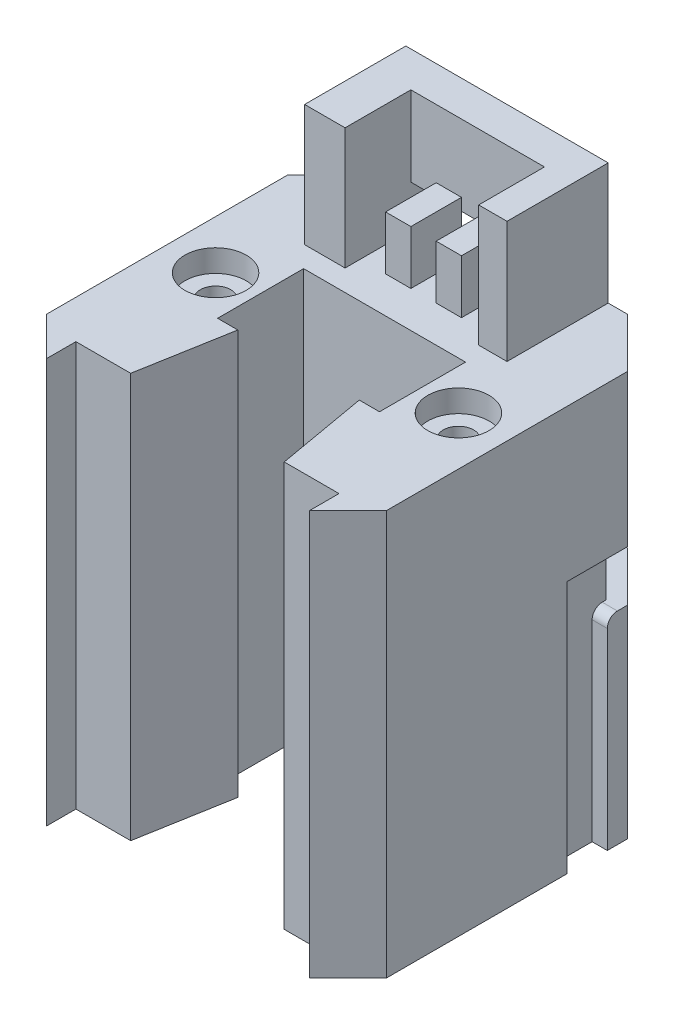
SolidWorks part; units mm, degrees
ref_plane "前视基准面" through (0, 0, 0) normal (0, 0, 1) x (1, 0, 0)
ref_plane "上视基准面" through (0, 0, 0) normal (0, 1, 0) x (1, 0, 0)
ref_plane "右视基准面" through (0, 0, 0) normal (1, 0, 0) x (0, 0, -1)
sketch "草图1" plane through (0, 0, 0) normal (0, 1, 0) x (1, 0, 0)
  line L0 (0, 0) -> (31, 0) construction
  line L1 (0, 0) -> (24.3952, -24.3952) construction
  line L2 (-31, 12) -> (-31, -12) construction
  line L3 (-32.8805, 15.9099) -> (-15.9099, 32.8805) construction
  line L4 (-24.3952, 24.3952) -> (0, 0) construction
  line L5 (-31, 0) -> (0, 0) construction
  line L6 (-43, 22.7609) -> (-43, -22.7609) construction
  line L7 (-43, 22.7609) -> (-22.7609, 43) construction
  line L8 (-24.3952, 24.3952) -> (-32.8805, 32.8805) construction
  line L9 (-31, 0) -> (-43, 0) construction
  line L10 (22.7609, 43) -> (43, 22.7609) construction
  line L11 (22.7609, 43) -> (-22.7609, 43) construction
  line L12 (43, -22.7609) -> (22.7609, -43) construction
  line L13 (43, -22.7609) -> (43, 22.7609) construction
  line L14 (-22.7609, -43) -> (-43, -22.7609) construction
  line L15 (-22.7609, -43) -> (22.7609, -43) construction
  line L16 (24.0036, 46) -> (-24.0036, 46) construction
  line L17 (-46, 24.0036) -> (-24.0036, 46) construction
  line L18 (-46, 24.0036) -> (-46, -24.0036) construction
  line L19 (-24.0036, -46) -> (-46, -24.0036) construction
  line L20 (-24.0036, -46) -> (24.0036, -46) construction
  line L21 (46, -24.0036) -> (24.0036, -46) construction
  line L22 (46, -24.0036) -> (46, 24.0036) construction
  line L23 (24.0036, 46) -> (46, 24.0036) construction
  line L24 (11.9085, 16.8) -> (-11.9085, 16.8)
  line L25 (-16.8, 11.9085) -> (-11.9085, 16.8)
  line L26 (-16.8, 11.9085) -> (-16.8, -11.9085)
  line L27 (-11.9085, -16.8) -> (-16.8, -11.9085)
  line L28 (-11.9085, -16.8) -> (11.9085, -16.8)
  line L29 (16.8, -11.9085) -> (11.9085, -16.8)
  line L30 (16.8, -11.9085) -> (16.8, 11.9085)
  line L31 (11.9085, 16.8) -> (16.8, 11.9085)
  circle A0 centre (0, 0) radius 15 construction
  circle A1 centre (31, 0) radius 12 construction
  circle A2 centre (24.3952, -24.3952) radius 12 construction
  circle A3 centre (0, -31) radius 12 construction
  circle A4 centre (-24.3952, -24.3952) radius 12 construction
  circle A5 centre (-31, 0) radius 12 construction
  circle A6 centre (-24.3952, 24.3952) radius 12 construction
  circle A7 centre (0, 31) radius 12 construction
  circle A8 centre (24.3952, 24.3952) radius 12 construction
  point P22 (0, 0)
  point P41 (0, 0)
  dimension "D1" = 30
  dimension "D2" = 24
  dimension "D3" = 31
  dimension "D4" = 34.5
  dimension "D5" = 45
  dimension "D8" = 3
  dimension "D9" = 26.2
  dimension "D6" = 4
  dimension "D7" = 4
extrude "凸台-拉伸1" add sketch "草图1" along normal blind 40
sketch "草图2" plane through (0, 40, 0) normal (0, 1, 0) x (1, 0, 0)
  line L0 (0, 0) -> (12, 0) construction
  line L1 (0, 0) -> (0, 18.2008) construction
  circle A0 centre (12, 0) radius 1.5
  circle A1 centre (-12, 0) radius 1.5
  dimension "D1" = 3
  dimension "D2" = 24
extrude "切除-拉伸1" cut sketch "草图2" against normal through all
sketch "草图3" plane through (0, 40, 0) normal (0, 1, 0) x (1, 0, 0)
  line L0 (0, 0) -> (0, -22.2905) construction
  line L1 (-6, -3.8) -> (6, -3.8)
  line L2 (6, -3.8) -> (7.5869, -12.8)
  line L3 (7.5869, -12.8) -> (13, -12.8)
  line L4 (13, -12.8) -> (13, -16.8)
  line L5 (-11.9085, -16.8) -> (11.9085, -16.8) construction
  line L6 (13, -16.8) -> (-13, -16.8)
  line L7 (-13, -12.8) -> (-13, -16.8)
  line L8 (-7.5869, -12.8) -> (-13, -12.8)
  line L9 (-6, -3.8) -> (-7.5869, -12.8)
  point P3 (11.3119, -16.8)
  point P12 (0, -16.8)
  point P15 (0, -3.8)
  point P16 (6, 3.6108)
  point P17 (6, 3.2457)
  point P18 (6, -4.8919)
  dimension "D1" = 13
  dimension "D2" = 12
  dimension "D3" = 4
  dimension "D4" = 26
  dimension "D5" = 100
extrude "切除-拉伸2" cut sketch "草图3" against normal through all
sketch "草图4" plane through (0, 40, 0) normal (0, 1, 0) x (1, 0, 0)
  line L0 (0, 0) -> (0, 19.1016) construction
  line L1 (11.9085, 16.8) -> (-11.9085, 16.8) construction
  line L2 (-10, 6.8) -> (10, 6.8)
  line L3 (-10, 6.8) -> (-10, 16.8)
  line L4 (-10, 16.8) -> (10, 16.8)
  line L5 (10, 6.8) -> (10, 16.8)
  line L6 (-10, 6.8) -> (10, 16.8) construction
  line L7 (-10, 16.8) -> (10, 6.8) construction
  line L9 (-6, 6.8) -> (7.2, 6.8)
  line L10 (-6, 6.8) -> (-6, 13.3)
  line L11 (-6, 13.3) -> (7.2, 13.3)
  line L12 (7.2, 6.8) -> (7.2, 13.3)
  point P3 (0, 11.8)
  line M13 (11.9085, 16.8) -> (-11.9085, 16.8)
  dimension "D1" = 20
  dimension "D2" = 10
  dimension "D3" = 3.5
  dimension "D4" = 13.2
  dimension "D5" = 4
extrude "凸台-拉伸2" add sketch "草图4" along normal blind 12 contours L12 L2 L5 L3 L10 L11 M13
sketch "草图5" plane through (0, 40, 0) normal (0, 1, 0) x (1, 0, 0)
  line L0 (0, 0) -> (0, 7.6634) construction
  line L1 (6, -3.8) -> (-6, -3.8) construction
  line L2 (-6, 4.7) -> (6, 4.7)
  line L3 (-6, 4.7) -> (-6, -3.8)
  line L4 (-6, -3.8) -> (6, -3.8)
  line L5 (6, 4.7) -> (6, -3.8)
  line L6 (-6, 4.7) -> (6, -3.8) construction
  line L7 (-6, -3.8) -> (6, 4.7) construction
  point P3 (0, 0.45)
  dimension "D1" = 12
  dimension "D2" = 8.5
extrude "切除-拉伸3" cut sketch "草图5" against normal through all
sketch "草图6" plane through (0, 0, 0) normal (0, -1, 0) x (1, 0, 0)
  line L0 (-6, -13.3) -> (7.2, -13.3) construction
  line L1 (-6, -13.3) -> (7.2, -13.3) construction
  line L2 (-6, -6.8) -> (-6, -13.3) construction
  line L3 (-6, -6.8) -> (-6, -13.3)
  line L4 (7.2, -6.8) -> (7.2, -13.3) construction
  line L5 (7.2, -6.8) -> (7.2, -13.3)
  line L6 (-6, -6.8) -> (-6, -4.7) construction
  line L7 (-6, -4.7) -> (6, -4.7) construction
  line L8 (6, -4.7) -> (7.2, -6.8) construction
  line L9 (-6, -6.8) -> (7.2, -6.8)
  line L10 (-6, -13.3) -> (-6, -16.8)
  line L11 (11.9085, -16.8) -> (-11.9085, -16.8) construction
  line L12 (-6, -16.8) -> (7.2, -16.8)
  line L13 (7.2, -16.8) -> (7.2, -13.3)
extrude "切除-拉伸4" cut sketch "草图6" against normal blind 12
sketch "草图7" plane through (0, 40, 0) normal (0, 1, 0) x (1, 0, 0)
  line L0 (-6, 13.3) -> (7.2, 13.3) construction
  line L1 (4, 13.3) -> (1.5, 13.3)
  line L2 (4, 13.3) -> (4, 8.3)
  line L3 (4, 8.3) -> (1.5, 8.3)
  line L4 (1.5, 13.3) -> (1.5, 8.3)
  line L6 (-1, 13.3) -> (-3.5, 13.3)
  line L7 (-1, 13.3) -> (-1, 8.3)
  line L8 (-1, 8.3) -> (-3.5, 8.3)
  line L9 (-3.5, 13.3) -> (-3.5, 8.3)
  line L10 (-6, 6.8) -> (-6, 13.3) construction
  dimension "D1" = 2.5
  dimension "D2" = 2.5
  dimension "D3" = 2.5
  dimension "D4" = 5
extrude "凸台-拉伸3" add sketch "草图7" along normal blind 5.3
sketch "草图8" plane through (0, 12, 0) normal (0, -1, 0) x (1, 0, 0)
  line L1 (-3.5, -11.8) -> (-1, -11.8)
  line L2 (-3.5, -11.8) -> (-3.5, -6.8)
  line L3 (-3.5, -6.8) -> (-1, -6.8)
  line L4 (-1, -11.8) -> (-1, -6.8)
  line L5 (-6, -6.8) -> (-6, -16.8) construction
  line L6 (1.5, -11.8) -> (4, -11.8)
  line L7 (1.5, -11.8) -> (1.5, -6.8)
  line L8 (1.5, -6.8) -> (4, -6.8)
  line L9 (4, -11.8) -> (4, -6.8)
  line L10 (7.2, -6.8) -> (-6, -6.8) construction
  point P4 (-3.5, -6.8)
  point P12 (0, 0)
  point P13 (0, 0)
  point P15 (1.5, -6.8)
  dimension "D1" = 2.5
  dimension "D2" = 2.5
  dimension "D3" = 2.5
  dimension "D4" = 5
extrude "凸台-拉伸4" add sketch "草图8" along normal blind 5.2
sketch "草图10" plane through (0, 40, 0) normal (0, 1, 0) x (1, 0, 0)
  line L0 (6, 0.45) -> (-6, 0.45) construction
  line L1 (6, -3.8) -> (6, 4.7) construction
  line L2 (-6, 4.7) -> (-6, -3.8) construction
  line L3 (6, 4.7) -> (-6, 4.7) construction
  line L4 (-8, -3.8) -> (8, -3.8)
  line L5 (-8, -3.8) -> (-8, 4.7)
  line L6 (-8, 4.7) -> (8, 4.7)
  line L7 (8, -3.8) -> (8, 4.7)
  line L8 (-8, -3.8) -> (8, 4.7) construction
  line L9 (-8, 4.7) -> (8, -3.8) construction
  point P6 (0, 0.45)
  point P11 (0, 0)
  dimension "D1" = 16
extrude "切除-拉伸5" cut sketch "草图10" against normal through all
sketch "草图11" plane through (0, 0, -13.3) normal (0, 0, 1) x (1, 0, 0)
  line L1 (-6, 52) -> (-6, 40) construction
  line L2 (1.5, 45.3) -> (-6, 45.3)
  line L3 (1.5, 45.3) -> (1.5, 40)
  line L4 (1.5, 40) -> (-6, 40)
  line L5 (-6, 45.3) -> (-6, 40)
  line L6 (-6, 44.1) -> (1.5, 44.1)
  dimension "D1" = 1.2
extrude "切除-拉伸6" cut sketch "草图11" against normal blind 11
sketch "草图15" plane through (0, 0, -16.8) normal (0, 0, -1) x (-1, 0, 0)
  line L0 (-1.5, 6.8) -> (-1.5, 12) construction
  line L1 (-1.5, 6.8) -> (-1.5, 12) construction
  line L2 (6, 12) -> (6, 0) construction
  line L3 (6, 12) -> (6, 0) construction
  line L5 (-1.5, 12) -> (6, 12)
  line L6 (-1.5, 12) -> (-1.5, 17)
  line L7 (-1.5, 17) -> (6, 17)
  line L8 (6, 12) -> (6, 17)
  point P7 (6.2201, 12)
  dimension "D1" = 5
extrude "切除-拉伸10" cut sketch "草图15" against normal up to surface (10 mm away) up to face at (0.3667, 8.2667, -6.8)
sketch "草图12" plane through (0, 40, 0) normal (0, 1, 0) x (1, 0, 0)
  line L0 (-6, 6.8) -> (-6, 16.8) construction
  line L1 (1.5, 16.8) -> (-6, 16.8)
  line L2 (1.5, 16.8) -> (1.5, 15.3)
  line L3 (1.5, 15.3) -> (-6, 15.3)
  line L4 (-6, 16.8) -> (-6, 15.3)
  dimension "D1" = 1.5
extrude "切除-拉伸7" cut sketch "草图12" against normal up to surface (28 mm away) up to face at (4.2333, 12, -11.8)
sketch "草图13" plane through (0, 0, 0) normal (0, -1, 0) x (1, 0, 0)
  line L0 (11.9085, -16.8) -> (1.5, -16.8)
  line L1 (1.5, -16.8) -> (7.2, -16.8) construction
  line L18 (1.5, -16.8) -> (7.2, -16.8) construction
  line L19 (11.9085, -16.8) -> (16.8, -11.9085)
  line L20 (16.8, -11.9085) -> (16.8, -5.9085)
  line L21 (16.8, 11.9085) -> (16.8, -11.9085) construction
  line L22 (15.3, -11.2872) -> (15.3, -5.9085)
  line L23 (11.2872, -15.3) -> (15.3, -11.2872)
  line L24 (11.2872, -15.3) -> (1.5, -15.3)
  line L25 (16.8, -5.9085) -> (15.3, -5.9085)
  line L26 (1.5, -16.8) -> (1.5, -15.3)
  dimension "D1" = 6
  dimension "D2" = 1.5
extrude "切除-拉伸8" cut sketch "草图13" against normal blind 5 from offset 20 offset against normal yes
fillet "圆角2" radius 2 1 edges at (-2.25, 17, -15.3)
sketch "草图16" plane through (0, 40, 0) normal (0, 1, 0) x (1, 0, 0)
  circle A0 centre (12, 0) radius 3.025
  circle A1 centre (-12, 0) radius 3.025
  dimension "D1" = 6.05
extrude "切除-拉伸11" cut sketch "草图16" against normal blind 2.2
ref_plane "基准面1" through (0, 20, 0) normal (0, 1, 0) x (1, 0, 0)
mirror "镜向1" about plane through (0, 20, 0) normal (0, 1, 0) of "切除-拉伸11"
sketch "草图17" plane through (0, 20, 0) normal (0, 1, 0) x (1, 0, 0)
  line L5 (15.3, 5.9085) -> (15.3, 11.2872) construction
  line L6 (16.8, 5.9085) -> (15.3, 5.9085)
  line L7 (16.8, 5.9085) -> (16.8, 9.9085)
  line L8 (16.8, 9.9085) -> (15.3, 9.9085)
  line L9 (15.3, 5.9085) -> (15.3, 9.9085)
  dimension "D1" = 4
extrude "切除-拉伸12" cut sketch "草图17" against normal through all
fillet "圆角3" radius 1 3 edges at (16.05, 20, -9.9085) (1.5, 20, -16.05) (1.5, 25, -16.05)
